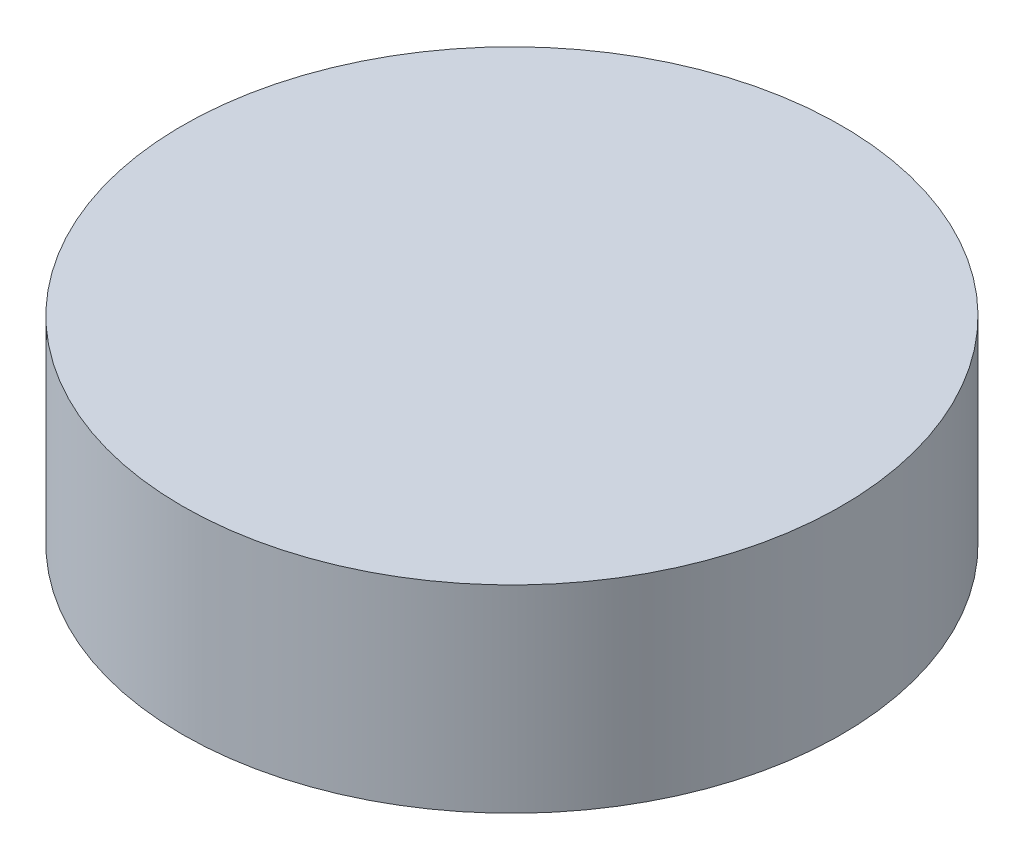
SolidWorks part; units mm, degrees
ref_plane "Front Plane" through (0, 0, 0) normal (0, 0, 1) x (1, 0, 0)
ref_plane "Top Plane" through (0, 0, 0) normal (0, 1, 0) x (1, 0, 0)
ref_plane "Right Plane" through (0, 0, 0) normal (1, 0, 0) x (0, 0, -1)
sketch "Sketch1" plane through (0, 0, 0) normal (0, 1, 0) x (1, 0, 0)
  circle A0 centre (0, 0) radius 0.04
extrude "Boss-Extrude1" add sketch "Sketch1" along normal blind 0.024
